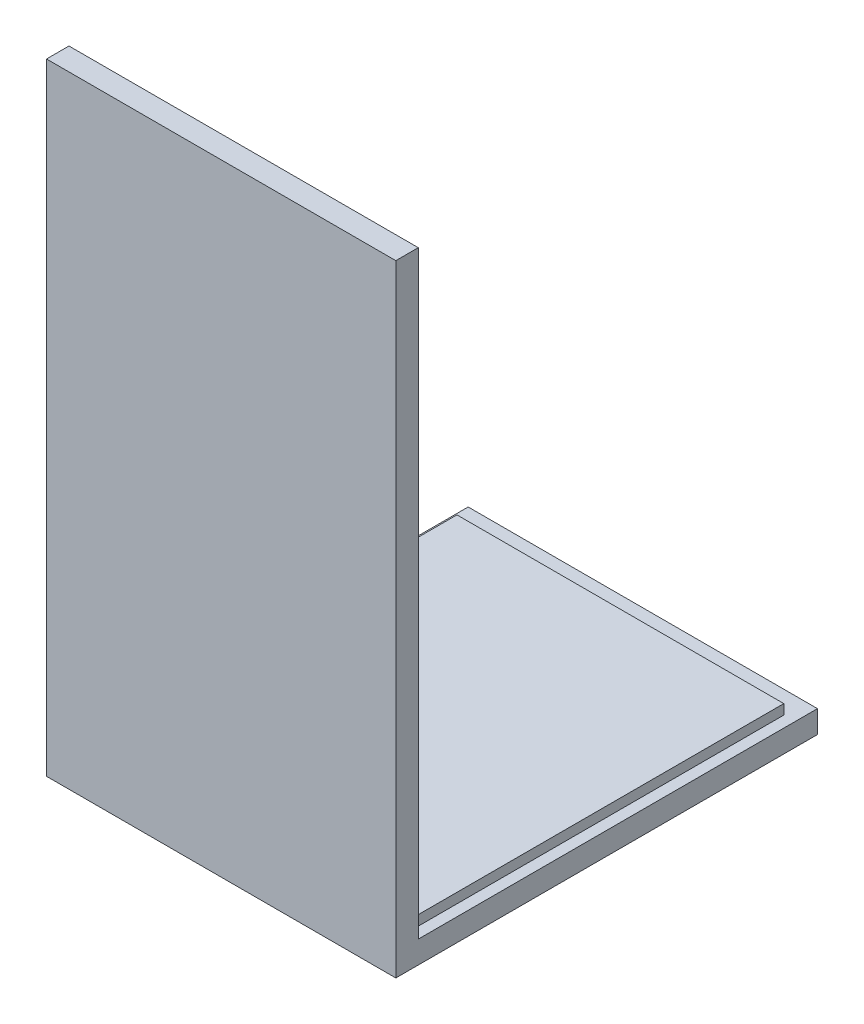
SolidWorks part; units mm, degrees
ref_plane "Front Plane" through (0, 0, 0) normal (1, 0, 0) x (0, 1, 0)
ref_plane "Top Plane" through (0, 0, 0) normal (0, 0, 1) x (0, 1, 0)
ref_plane "Right Plane" through (0, 0, 0) normal (0, 1, 0) x (-1, 0, 0)
sketch "Sketch1" plane through (0, 0, 0) normal (0, 0, 1) x (0, 1, 0)
  line L1 (0, 0) -> (124.5, 0)
  line L2 (0, 0) -> (0, 70)
  line L3 (0, 70) -> (124.5, 70)
  line L4 (124.5, 0) -> (124.5, 70)
  dimension "D1" = 70
  dimension "D2" = 124.5
extrude "Boss-Extrude1" add sketch "Sketch1" along normal blind 4.5
sketch "Sketch2" plane through (0, 0, 0) normal (0, 0, -1) x (1, 0, 0)
  line L0 (0, 0) -> (0, -124.5) construction
  line L1 (-70, 0) -> (0, 0)
  line L2 (-70, 0) -> (-70, -4.5)
  line L3 (-70, -4.5) -> (0, -4.5)
  line L4 (0, 0) -> (0, -4.5)
  dimension "D1" = 4.5
extrude "Boss-Extrude2" add sketch "Sketch2" along normal blind 80
sketch "Sketch3" plane through (0, 0, 0) normal (0, 0, -1) x (1, 0, 0)
  line L0 (-70, -4.5) -> (0, -4.5) construction
  line L1 (-67.75, -4.5) -> (-2.25, -4.5)
  line L2 (-67.75, -4.5) -> (-67.75, -6.5)
  line L3 (-67.75, -6.5) -> (-2.25, -6.5)
  line L4 (-2.25, -4.5) -> (-2.25, -6.5)
  line L5 (-35, -124.5) -> (-35, -4.5) construction
  line L6 (0, -124.5) -> (-70, -124.5) construction
  line L7 (-70, -124.5) -> (-70, -4.5) construction
  line L8 (0, 0) -> (0, -124.5) construction
  point P10 (0, 0)
  point P11 (0, 0)
  point P12 (0, 0)
  point P13 (0, 0)
  dimension "D1" = 2.25
  dimension "D2" = 2.25
  dimension "D3" = 2
extrude "Boss-Extrude3" add sketch "Sketch3" along normal offset from surface (75.5 mm away) 4.5 up to face at (-35, 2.25, -80)
